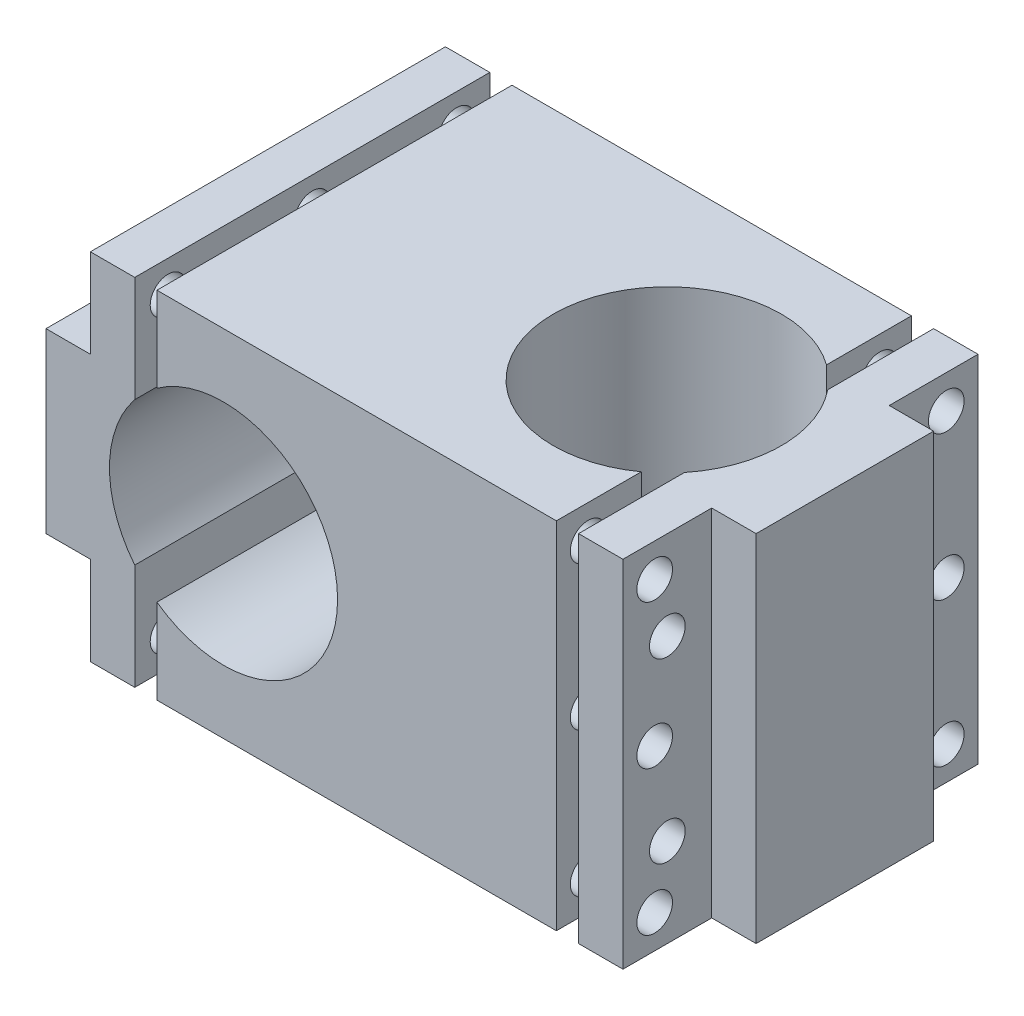
SolidWorks part; units mm, degrees
material "PE High Density"
ref_plane "Front" through (0, 0, 0) normal (0, 0, 1) x (1, 0, 0)
ref_plane "Top" through (0, 0, 0) normal (0, 1, 0) x (1, 0, 0)
ref_plane "Right" through (0, 0, 0) normal (1, 0, 0) x (0, 0, -1)
sketch "Sketch1" plane through (0, 0, 0) normal (0, 1, 0) x (1, 0, 0)
  line L1 (-44.45, -25.4) -> (44.45, -25.4)
  line L2 (-44.45, -25.4) -> (-44.45, 25.4)
  line L3 (-44.45, 25.4) -> (44.45, 25.4)
  line L4 (44.45, -25.4) -> (44.45, 25.4)
  line L5 (-44.45, -25.4) -> (44.45, 25.4) construction
  line L6 (-44.45, 25.4) -> (44.45, -25.4) construction
  point P0 (0, 0)
  dimension "D1" = 50.8
  dimension "D2" = 88.9
extrude "Boss-Extrude1" add sketch "Sketch1" along normal mid plane 50.8 contours L3 L4 L1 L2
sketch "Sketch2" plane through (0, 25.4, 0) normal (0, 1, 0) x (1, 0, 0)
  line L0 (-50, 0) -> (50, 0) construction
  line L1 (44.45, -25.4) -> (44.45, 25.4) construction
  circle A0 centre (19.05, 0) radius 16.3195
  dimension "D1" = 32.639
  dimension "D2" = 25.4
extrude "Cut-Extrude1" cut sketch "Sketch2" against normal up to next
sketch "Sketch3" plane through (0, 25.4, 0) normal (0, 1, 0) x (1, 0, 0)
  line L0 (-44.45, 25.4) -> (44.45, 25.4) construction
  line L1 (28.575, -28.2952) -> (31.75, -28.2952)
  line L2 (28.575, -28.2952) -> (28.575, 25.4)
  line L3 (28.575, 25.4) -> (31.75, 25.4)
  line L4 (31.75, -28.2952) -> (31.75, 25.4)
  line L5 (28.575, -28.2952) -> (31.75, 25.4) construction
  line L6 (28.575, 25.4) -> (31.75, -28.2952) construction
  line L7 (44.45, -25.4) -> (44.45, 25.4) construction
  point P0 (30.1625, -1.4476)
  point P9 (0, 0)
  dimension "D1" = 12.7
  dimension "D2" = 3.175
extrude "Cut-Extrude4" cut sketch "Sketch3" against normal blind 50.8 contours L2 L3 L4 L1
sketch "Sketch4" plane through (44.45, 0, 0) normal (1, 0, 0) x (0, 0, -1)
  line L0 (20.8597, 20.6375) -> (20.8597, -20.6375) construction
  line L1 (50, 0) -> (-50, 0) construction
  line L2 (25.4, 25.4) -> (25.4, -25.4) construction
  point P0 (20.8597, 20.6375)
  point P1 (20.8597, -20.6375)
  point P10 (20.8597, 0)
  dimension "D1" = 41.275
  dimension "D2" = 4.5403
hole_wizard "1/4-20 Tapped Hole1" positions "Sketch5" profile "Sketch6" tap size "1/4-20" standard "ANSI Inch"
sketch "Sketch5" plane through (44.45, 0, 0) normal (1, 0, 0) x (0, 0, -1)
  point P0 (20.8597, 20.6375)
  point P3 (20.8597, -20.6375)
  point P6 (20.8597, 0)
sketch "Sketch6" plane through (44.45, 20.6375, -20.8597) normal (0, 1, 0) x (0, 0, -1)
  line L0 (0, 0) -> (0, 26.9338)
  line L1 (0, 26.9338) -> (2.5527, 25.4)
  line L2 (2.5527, 25.4) -> (2.5527, 0)
  line L5 (2.5527, 0) -> (0, 0)
  line L10 (0, 26.9338) -> (-2.5527, 25.4) construction
  line L11 (0, -6.35) -> (0, 107.95) construction
  dimension "Tap Drill Dia." = 5.1054
  dimension "Tap Drill Depth" = 25.4
  dimension "Drill Angle" = 118
cosmetic thread "Hole Thread6" parameters "D1"=12.7, "D2"=6.35
cosmetic thread "Hole Thread7" parameters "D1"=12.7, "D2"=6.35
cosmetic thread "Hole Thread8" parameters "D1"=12.7, "D2"=6.35
sketch "Sketch7" plane through (0, 0, 25.4) normal (0, 0, 1) x (1, 0, 0)
  line L0 (50, 0) -> (-50, 0) construction
  line L1 (-44.45, 25.4) -> (-44.45, -25.4) construction
  circle A0 centre (-19.05, 0) radius 16.3195
  dimension "D1" = 32.639
  dimension "D2" = 25.4
extrude "Cut-Extrude5" cut sketch "Sketch7" against normal blind 50.8
sketch "Sketch8" plane through (0, 0, 25.4) normal (0, 0, 1) x (1, 0, 0)
  line L0 (-44.45, -25.4) -> (28.575, -25.4) construction
  line L1 (-31.75, -25.4) -> (-28.575, -25.4)
  line L2 (-31.75, -25.4) -> (-31.75, 31.3456)
  line L3 (-31.75, 31.3456) -> (-28.575, 31.3456)
  line L4 (-28.575, -25.4) -> (-28.575, 31.3456)
  line L5 (-31.75, -25.4) -> (-28.575, 31.3456) construction
  line L6 (-31.75, 31.3456) -> (-28.575, -25.4) construction
  line L7 (-44.45, 25.4) -> (-44.45, -25.4) construction
  point P0 (-30.1625, 2.9728)
  point P9 (0, 0)
  dimension "D1" = 12.7
  dimension "D2" = 3.175
extrude "Cut-Extrude6" cut sketch "Sketch8" against normal blind 50.8
ref_plane "Plane1" [suppressed] through (0, -19.3257, 0) normal (0, 1, 0) x (1, 0, 0)
sketch "Sketch9" plane through (-44.45, 0, 0) normal (-1, 0, 0) x (0, 0, 1)
  line L0 (-20.6375, -20.8597) -> (20.6375, -20.8598) construction
  line L1 (0, -50) -> (0, 50) construction
  line L4 (25.4, -25.4) -> (-25.4, -25.4) construction
  point P0 (-20.6375, -20.8597)
  point P1 (20.6375, -20.8597)
  point P4 (55.4876, -28.9435)
  point P10 (0, -20.8597)
  dimension "D1" = 41.275
  dimension "D2" = 4.5403
hole_wizard "1/4-20 Tapped Hole2" positions "Sketch10" profile "Sketch11" tap size "1/4-20" standard "ANSI Inch"
sketch "Sketch10" plane through (-44.45, 0, 0) normal (-1, 0, 0) x (0, 0, 1)
  point P0 (-20.6375, -20.8597)
  point P3 (20.6375, -20.8597)
  point P6 (0, -20.8597)
sketch "Sketch11" plane through (-44.45, -20.8597, -20.6375) normal (0, 1, 0) x (0, 0, 1)
  line L0 (0, 0) -> (0, 26.9338)
  line L1 (0, 26.9338) -> (2.5527, 25.4)
  line L2 (2.5527, 25.4) -> (2.5527, 0)
  line L5 (2.5527, 0) -> (0, 0)
  line L10 (0, 26.9338) -> (-2.5527, 25.4) construction
  line L11 (0, -6.35) -> (0, 107.95) construction
  dimension "Tap Drill Dia." = 5.1054
  dimension "Tap Drill Depth" = 25.4
  dimension "Drill Angle" = 118
cosmetic thread "Hole Thread9" parameters "D1"=12.7, "D2"=6.35
cosmetic thread "Hole Thread10" parameters "D1"=12.7, "D2"=6.35
cosmetic thread "Hole Thread11" parameters "D1"=12.7, "D2"=6.35
sketch "Sketch12" plane through (0, 25.4, 0) normal (0, 1, 0) x (1, 0, 0)
  line L0 (-19.05, 12.7) -> (-19.05, -12.7) construction
  line L1 (-50, 0) -> (50, 0) construction
  line L2 (-44.45, -25.4) -> (-44.45, 25.4) construction
  point P0 (-19.05, 12.7)
  point P1 (-19.05, -12.7)
  point P4 (-19.05, 0)
  dimension "D1" = 25.4
  dimension "D2" = 25.4
hole_wizard "1/4-20 Tapped Hole3" [suppressed] positions "3DSketch1" profile "Sketch13" tap size "1/4-20" standard "ANSI Inch"
sketch3d "3DSketch1"
  point P0 (-19.05, 25.4, -12.7)
  point P3 (-19.05, 25.4, 12.7)
sketch "Sketch13" plane through (-19.05, 25.4, -12.7) normal (1, 0, 0) x (0, 0, 1)
  line L0 (0, 0) -> (0, 26.9338)
  line L1 (0, 26.9338) -> (2.5527, 25.4)
  line L2 (2.5527, 25.4) -> (2.5527, 0)
  line L5 (2.5527, 0) -> (0, 0)
  line L10 (0, 26.9338) -> (-2.5527, 25.4) construction
  line L11 (0, -6.35) -> (0, 107.95) construction
  dimension "Tap Drill Dia." = 5.1054
  dimension "Tap Drill Depth" = 25.4
  dimension "Drill Angle" = 118
hole_wizard "CBORE for 1/4 Socket Head Cap Screw1" [suppressed] positions "Sketch14" profile "Sketch16" counterbore size "1/4" standard "ANSI Inch"
sketch "Sketch14" plane through (44.45, 0, 0) normal (1, 0, 0) x (0, 0, -1)
  point P0 (20.8597, 19.05)
  point P3 (20.8597, -19.05)
sketch "Sketch16" plane through (44.45, 19.05, -20.8597) normal (0, 1, 0) x (0, 0, -1)
  line L0 (0, 0) -> (0, 14.7298)
  line L1 (0, 14.7298) -> (3.3782, 12.7)
  line L2 (3.3782, 12.7) -> (3.3782, 6.35)
  line L3 (3.3782, 6.35) -> (5.5562, 6.35)
  line L4 (5.5562, 6.35) -> (5.5562, 0)
  line L5 (5.5562, 0) -> (0, 0)
  line L10 (0, 14.7298) -> (-3.3782, 12.7) construction
  line L11 (0, -6.35) -> (0, 107.95) construction
  dimension "Hole Dia." = 6.7564
  dimension "Hole Depth" = 12.7
  dimension "C'Bore Dia." = 11.1125
  dimension "C'Bore Depth" = 6.35
  dimension "Drill Angle" = 118
hole_wizard "CBORE for 1/4 Socket Head Cap Screw2" [suppressed] positions "Sketch17" profile "Sketch18" counterbore size "1/4" standard "ANSI Inch"
sketch "Sketch17" plane through (-44.45, 0, 0) normal (-1, 0, 0) x (0, 0, 1)
  point P0 (-12.7, -20.8597)
  point P3 (12.7, -20.8598)
sketch "Sketch18" plane through (-44.45, -20.8597, -12.7) normal (0, 1, 0) x (0, 0, 1)
  line L0 (0, 0) -> (0, 14.7298)
  line L1 (0, 14.7298) -> (3.3782, 12.7)
  line L2 (3.3782, 12.7) -> (3.3782, 6.35)
  line L3 (3.3782, 6.35) -> (5.5562, 6.35)
  line L4 (5.5562, 6.35) -> (5.5562, 0)
  line L5 (5.5562, 0) -> (0, 0)
  line L10 (0, 14.7298) -> (-3.3782, 12.7) construction
  line L11 (0, -6.35) -> (0, 107.95) construction
  dimension "Hole Dia." = 6.7564
  dimension "Hole Depth" = 12.7
  dimension "C'Bore Dia." = 11.1125
  dimension "C'Bore Depth" = 6.35
  dimension "Drill Angle" = 118
sketch "Sketch19" plane through (44.45, 0, 0) normal (1, 0, 0) x (0, 0, -1)
  line L0 (-19.05, 12.7) -> (-19.05, -12.7) construction
  line L1 (50, 0) -> (-50, 0) construction
  line L2 (-25.4, 25.4) -> (-25.4, -25.4) construction
  line L3 (-20.8598, 20.6375) -> (-20.8597, -20.6375) construction
  point P2 (-19.05, 0)
  point P7 (-20.8597, 0)
  point P10 (-20.8597, 0)
  dimension "D1" = 25.4
  dimension "D2" = 6.35
  dimension "D3" = 4.5403
  dimension "D4" = 41.275
hole_wizard "1/4-20 Tapped Hole4" positions "Sketch20" profile "Sketch22" tap size "1/4-20" standard "ANSI Inch"
sketch "Sketch20" plane through (44.45, 0, 0) normal (1, 0, 0) x (0, 0, -1)
  point P0 (-19.05, 12.7)
  point P3 (-19.05, -12.7)
  point P7 (-20.8597, 0)
  point P11 (-20.8598, 20.6375)
  point P14 (-20.8597, -20.6375)
sketch "Sketch22" plane through (44.45, 12.7, 19.05) normal (0, 1, 0) x (0, 0, -1)
  line L0 (0, 0) -> (0, 26.9338)
  line L1 (0, 26.9338) -> (2.5527, 25.4)
  line L2 (2.5527, 25.4) -> (2.5527, 0)
  line L5 (2.5527, 0) -> (0, 0)
  line L10 (0, 26.9338) -> (-2.5527, 25.4) construction
  line L11 (0, -6.35) -> (0, 107.95) construction
  dimension "Tap Drill Dia." = 5.1054
  dimension "Tap Drill Depth" = 25.4
  dimension "Drill Angle" = 118
cosmetic thread "Hole Thread1" parameters "D1"=12.7, "D2"=6.35
cosmetic thread "Hole Thread2" parameters "D1"=12.7, "D2"=6.35
cosmetic thread "Hole Thread3" parameters "D1"=12.7, "D2"=6.35
cosmetic thread "Hole Thread4" parameters "D1"=12.7, "D2"=6.35
cosmetic thread "Hole Thread5" parameters "D1"=12.7, "D2"=6.35
sketch "Sketch26" plane through (-44.45, 0, 0) normal (-1, 0, 0) x (0, 0, 1)
  line L0 (0, -50) -> (0, 50) construction
  line L1 (-12.7, 19.05) -> (12.7, 19.05) construction
  line L2 (-20.6375, 20.8597) -> (20.6375, 20.8598) construction
  line L3 (25.4, 25.4) -> (-25.4, 25.4) construction
  point P0 (0, 20.8597)
  point P7 (0, 20.8597)
  point P8 (0, 19.05)
  dimension "D1" = 25.4
  dimension "D2" = 41.275
  dimension "D3" = 4.5403
  dimension "D4" = 6.35
hole_wizard "1/4-20 Tapped Hole5" positions "Sketch27" profile "Sketch28" tap size "1/4-20" standard "ANSI Inch"
sketch "Sketch27" plane through (-44.45, 0, 0) normal (-1, 0, 0) x (0, 0, 1)
  point P0 (0, 20.8597)
  point P3 (-12.7, 19.05)
  point P6 (-20.6375, 20.8597)
  point P9 (12.7, 19.05)
  point P12 (20.6375, 20.8598)
sketch "Sketch28" plane through (-44.45, 20.8597, 0) normal (0, 1, 0) x (0, 0, 1)
  line L0 (0, 0) -> (0, 26.9338)
  line L1 (0, 26.9338) -> (2.5527, 25.4)
  line L2 (2.5527, 25.4) -> (2.5527, 0)
  line L5 (2.5527, 0) -> (0, 0)
  line L10 (0, 26.9338) -> (-2.5527, 25.4) construction
  line L11 (0, -6.35) -> (0, 107.95) construction
  dimension "Tap Drill Dia." = 5.1054
  dimension "Tap Drill Depth" = 25.4
  dimension "Drill Angle" = 118
cosmetic thread "Hole Thread12" parameters "D1"=12.7, "D2"=6.35
cosmetic thread "Hole Thread13" parameters "D1"=12.7, "D2"=6.35
cosmetic thread "Hole Thread14" parameters "D1"=12.7, "D2"=6.35
cosmetic thread "Hole Thread15" parameters "D1"=12.7, "D2"=6.35
cosmetic thread "Hole Thread16" parameters "D1"=12.7, "D2"=6.35
sketch "Sketch29" plane through (-44.45, 0, 0) normal (-1, 0, 0) x (0, 0, 1)
  line L0 (25.4, 25.4) -> (25.4, -25.4) construction
  line L1 (-25.4, 25.4) -> (25.4, 25.4)
  line L2 (-25.4, 25.4) -> (-25.4, 12.7)
  line L3 (-25.4, 12.7) -> (25.4, 12.7)
  line L4 (25.4, 25.4) -> (25.4, 12.7)
  dimension "D1" = 12.7
extrude "Cut-Extrude7" cut sketch "Sketch29" against normal blind 6.35
mirror "Mirror1" about plane through (0, 0, 0) normal (0, 1, 0) of "Cut-Extrude7"
sketch "Sketch30" plane through (44.45, 0, 0) normal (1, 0, 0) x (0, 0, -1)
  line L0 (-25.4, -25.4) -> (25.4, -25.4) construction
  line L1 (-25.4, 25.4) -> (-12.7, 25.4)
  line L2 (-25.4, 25.4) -> (-25.4, -25.4)
  line L3 (-25.4, -25.4) -> (-12.7, -25.4)
  line L4 (-12.7, 25.4) -> (-12.7, -25.4)
  dimension "D1" = 12.7
extrude "Cut-Extrude8" cut sketch "Sketch30" against normal blind 6.35
mirror "Mirror2" about plane through (0, 0, 0) normal (0, 0, 1) of "Cut-Extrude8"
